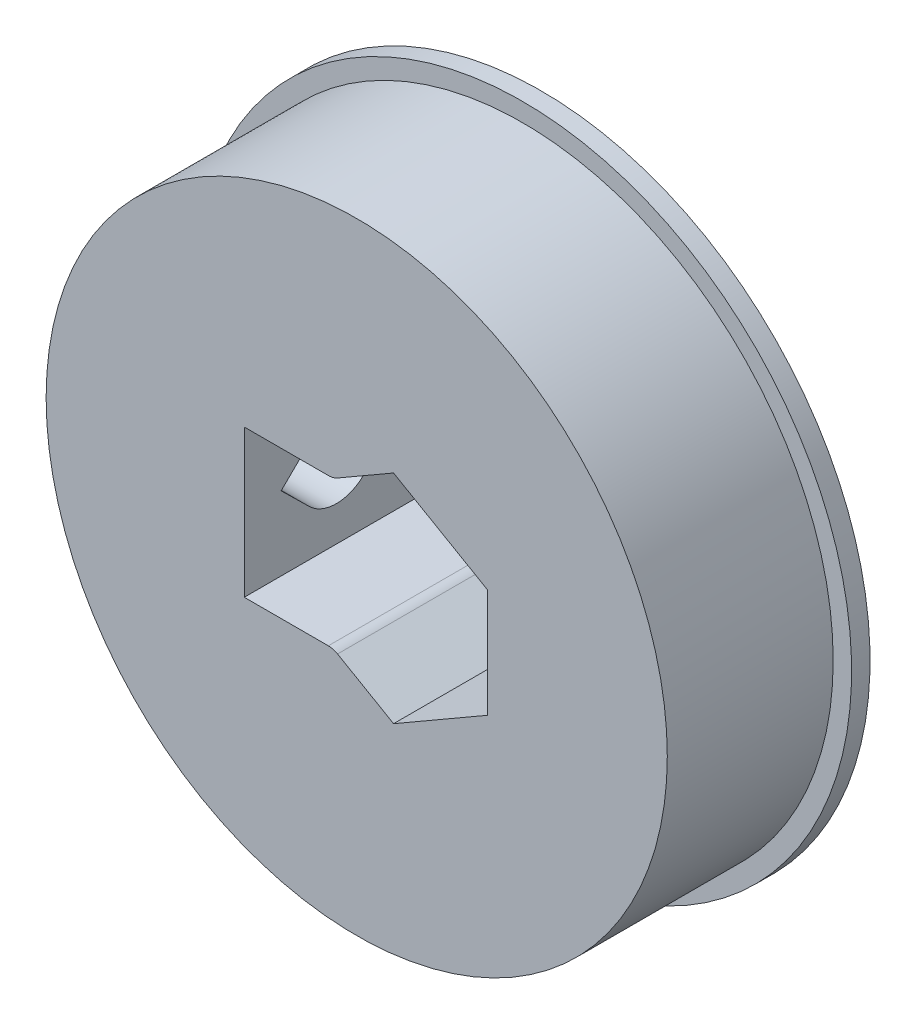
SolidWorks part; units mm, degrees
material "ABS"
ref_plane "Front Plane" through (0, 0, 0) normal (0, 0, 1) x (1, 0, 0)
ref_plane "Top Plane" through (0, 0, 0) normal (0, 1, 0) x (1, 0, 0)
ref_plane "Right Plane" through (0, 0, 0) normal (1, 0, 0) x (0, 0, -1)
sketch "Sketch1" plane through (0, 0, 0) normal (0, 0, 1) x (1, 0, 0)
  line L0 (0, 0) -> (-1, 0) construction
  line L1 (0, -2.9445) -> (2.55, -1.4722)
  line L2 (2.55, -1.4722) -> (2.55, 1.4722)
  line L3 (2.55, 1.4722) -> (0, 2.9445)
  line L4 (0, 2.9445) -> (-2.55, 1.4722)
  line L5 (-2.55, 1.4722) -> (-2.55, -1.4722)
  line L6 (-2.55, -1.4722) -> (0, -2.9445)
  circle A0 centre (0, 0) radius 2.55 construction
  circle A1 centre (-1, 0) radius 8.425
  dimension "D1" = 5.1
  dimension "D3" = 16.85
  dimension "D2" = 1
extrude "Boss-Extrude1" add sketch "Sketch1" along normal blind 5 contours A1
sketch "Sketch2" plane through (-2.55, 0, 0) normal (1, 0, 0) x (0, 0, -1)
  line L0 (0, 0) -> (-5, 0) construction
  line L1 (-0.1906, 0) -> (-1.3453, 2) construction
  line L2 (-1.3453, 2) -> (-3.6547, 2) construction
  line L3 (-3.6547, 2) -> (-4.8094, 0) construction
  line L4 (-4.8094, 0) -> (-3.6547, -2) construction
  line L5 (-3.6547, -2) -> (-1.3453, -2) construction
  line L6 (-1.3453, -2) -> (-0.1906, 0) construction
  line L7 (0, 1.4722) -> (0, -1.4722) construction
  line L8 (-5, 1.4722) -> (-5, -1.4722) construction
  line L10 (0, -2) -> (-5, -2)
  line L11 (0, -2) -> (0, 2)
  line L12 (0, 2) -> (-5, 2)
  line L13 (-5, -2) -> (-5, 2)
  line L14 (0, -2) -> (-5, 2) construction
  line L15 (0, 2) -> (-5, -2) construction
  circle A0 centre (-2.5, 0) radius 2 construction
  dimension "D1" = 4
extrude "M2 Hexnut Cutout" cut sketch "Sketch2" against normal blind 1.5 and the other way blind 1.5
fillet "Fillet1" radius 0.5 2 edges at (-1.6359, -2, 2.5) (-1.6359, 2, 2.5)
sketch "Sketch3" plane through (-4.05, 0, 0) normal (1, 0, 0) x (0, 0, -1)
  line L0 (0, 0) -> (-5, 0) construction
  line L1 (0, -2) -> (0, 2) construction
  line L2 (-5, 2) -> (-5, -2) construction
  line L3 (-2.5, 0) -> (-1, 0) construction
  line L4 (-1, 0) -> (-1.765, 0.7498)
  line L5 (-1, 0) -> (-1.765, -0.7498)
  line L6 (-1, 0) -> (-1.765, -0.7498)
  line L7 (-1, 0) -> (-1.765, 0.7498)
  line L8 (-2.5, 0) -> (-2.5, 1.4001) construction
  line L9 (-4, 0) -> (-3.235, -0.7498)
  line L10 (-4, 0) -> (-3.235, 0.7498)
  arc A0 (-1.765, 0.7498) -> (-3.235, 0.7498) centre (-2.5, 0) ccw
  arc A1 (-1.765, 0.7498) -> (-3.235, 0.7498) centre (-2.5, 0) ccw
  arc A2 (-3.235, -0.7498) -> (-1.765, -0.7498) centre (-2.5, 0) ccw
  arc A3 (-3.235, -0.7498) -> (-1.765, -0.7498) centre (-2.5, 0) ccw
  dimension "D1" = 1.5
  dimension "M2 Thru" = 2.1
extrude "M2 Thru" cut sketch "Sketch3" against normal through all contours L9 A2 L5 L4 A0 L10
sketch "Sketch4" plane through (0, 0, 0) normal (0, 0, -1) x (-1, 0, 0)
  circle A0 centre (1, 0) radius 8.425
  circle A1 centre (1, 0) radius 8.925
  circle A2 centre (1, 0) radius 8.425 construction
  dimension "D1" = 17.85
  dimension "D2" = 16.85
extrude "Boss-Extrude2" add sketch "Sketch4" against normal blind 0.5
equation "\"D1@Sketch4\"=\"D2@Sketch4\"+1"
